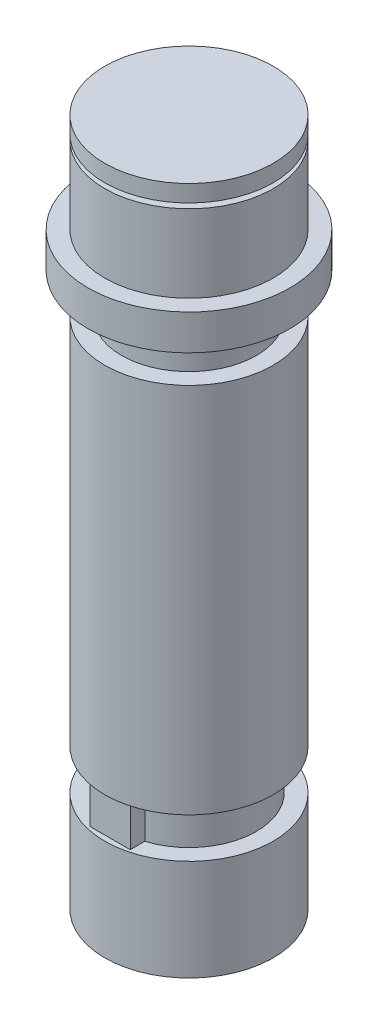
SolidWorks part; units mm, degrees
ref_plane "Front Plane" through (0, 0, 0) normal (0, 0, 1) x (1, 0, 0)
ref_plane "Top Plane" through (0, 0, 0) normal (0, 1, 0) x (1, 0, 0)
ref_plane "Right Plane" through (0, 0, 0) normal (1, 0, 0) x (0, 0, -1)
sketch "Sketch1" plane through (0, 0, 0) normal (0, 1, 0) x (1, 0, 0)
  line L0 (-5.969, -19.0885) -> (-5.969, -23.4065)
  line L1 (-5.969, -23.4065) -> (5.969, -23.4065)
  line L2 (5.969, -23.4065) -> (5.969, -19.0885)
  circle A0 centre (0, 0) radius 20
  arc A1 (-5.969, -19.0885) -> (5.969, -19.0885) centre (0, 0) ccw
  dimension "D1" = 40
  dimension "D2" = 11.938
  dimension "D3" = 4.318
  dimension "D4" = 4.318
extrude "Boss-Extrude4" add sketch "Sketch1" along normal blind 11.938 contours A0 | L1 L2 A1 L0
sketch "Sketch2" plane through (0, 0, 0) normal (0, 1, 0) x (1, 0, 0)
  circle A0 centre (0, 0) radius 25
  dimension "D1" = 50
extrude "Boss-Extrude8" add sketch "Sketch2" against normal blind 30
sketch "Sketch7" plane through (0, 11.938, 0) normal (0, 1, 0) x (1, 0, 0)
  circle A0 centre (0, 0) radius 25
extrude "Boss-Extrude9" add sketch "Sketch7" along normal blind 110.4
sketch "Sketch8" plane through (0, 122.338, 0) normal (0, 1, 0) x (1, 0, 0)
  circle A0 centre (0, 0) radius 20
  dimension "D1" = 40
extrude "Boss-Extrude11" add sketch "Sketch8" along normal blind 11.9
sketch "Sketch9" plane through (0, 134.238, 0) normal (0, 1, 0) x (1, 0, 0)
  line L0 (-5.95, 19.0944) -> (-5.95, 23.3944)
  line L1 (-5.95, 23.3944) -> (5.95, 23.3944)
  line L2 (5.95, 23.3944) -> (5.95, 19.0944)
  circle A0 centre (0, 0) radius 20 construction
  circle A1 centre (0, 0) radius 20 construction
  arc A2 (-5.95, 19.0944) -> (5.95, 19.0944) centre (0, 0) cw
  dimension "D1" = 11.9
  dimension "D2" = 4.3
  dimension "D3" = 4.3
extrude "Boss-Extrude12" add sketch "Sketch9" against normal blind 12.9
sketch "Sketch12" plane through (0, 134.238, 0) normal (0, 1, 0) x (1, 0, 0)
  circle A0 centre (0, 0) radius 30
  dimension "D1" = 60
extrude "Boss-Extrude14" add sketch "Sketch12" along normal blind 10.5
sketch "Sketch14" plane through (0, 144.738, 0) normal (0, 1, 0) x (1, 0, 0)
  circle A0 centre (0, 0) radius 25
  dimension "D1" = 50
extrude "Boss-Extrude15" add sketch "Sketch14" along normal blind 23
sketch "Sketch15" plane through (0, 167.738, 0) normal (0, 1, 0) x (1, 0, 0)
  circle A0 centre (0, 8) radius 5
  circle A1 centre (0, -8) radius 5
  circle A3 centre (0, 0) radius 25 construction
  dimension "D1" = 10
  dimension "D2" = 10
  dimension "D3" = 16
  dimension "D4" = 8
extrude "Boss-Extrude17" add sketch "Sketch15" along normal blind 1.5
sketch "Sketch17" plane through (0, 169.238, 0) normal (0, 1, 0) x (1, 0, 0)
  circle A0 centre (0, 0) radius 25
extrude "Boss-Extrude21" add sketch "Sketch17" along normal blind 5
